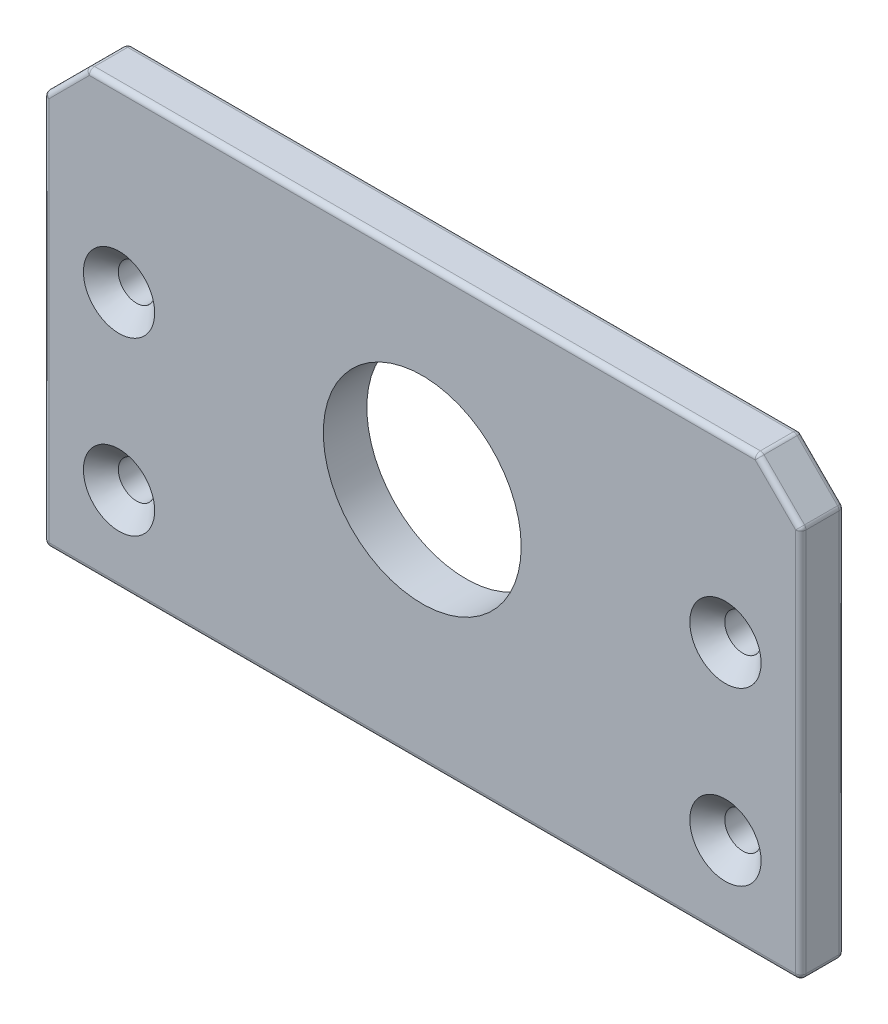
SolidWorks part; units mm, degrees
ref_plane "Front Plane" through (0, 0, 0) normal (0, 0, 1) x (1, 0, 0)
ref_plane "Top Plane" through (0, 0, 0) normal (0, 1, 0) x (1, 0, 0)
ref_plane "Right Plane" through (0, 0, 0) normal (1, 0, 0) x (0, 0, -1)
sketch "Sketch2" plane through (0, 0, 0) normal (0, 1, 0) x (1, 0, 0)
  line L1 (-55.245, 3.175) -> (55.245, 3.175)
  line L2 (-55.245, 3.175) -> (-55.245, -3.175)
  line L3 (-55.245, -3.175) -> (55.245, -3.175)
  line L4 (55.245, 3.175) -> (55.245, -3.175)
  point P4 (0, 3.175)
  point P7 (-55.245, 0)
  dimension "D1" = 6.35
  dimension "D2" = 110.49
extrude "Boss-Extrude1" add sketch "Sketch2" against normal blind 63.5
sketch "Sketch3" plane through (0, 0, 3.175) normal (0, 0, 1) x (1, 0, 0)
  line L2 (-55.245, 0) -> (55.245, 0) construction
  circle A0 centre (0, -28.815) radius 14.4375
  point P2 (0, 0)
  dimension "D1" = 28.815
  dimension "D3" = 28.875
extrude "Cut-Extrude1" cut sketch "Sketch3" against normal through all
chamfer "Chamfer1" distance 6.35 angle 45 2 edges at (-55.245, 0, 0) (55.245, 0, 0)
fillet "Fillet1" [suppressed] radius 0.762
hole_wizard "CBORE for M4 SHCS2" [suppressed] positions "Sketch9" profile "Sketch10" counterbore size "M4" standard "ANSI Metric"
sketch "Sketch9" [suppressed] plane through (0, 0, 3.175) normal (0, 0, 1) x (1, 0, 0)
  line L0 (-48.5794, 0) -> (48.5794, 0) construction
  line L1 (-55.245, -62.738) -> (-55.245, -6.6656) construction
  point P0 (-17.9605, -10.8545)
  dimension "D1" = 10.8545
  dimension "D2" = 37.2845
sketch "Sketch10" plane through (-17.9605, -10.8545, 3.175) normal (1, 0, 0) x (0, -1, 0)
  line L0 (0, 0) -> (0, 6.35)
  line L1 (0, 6.35) -> (2.25, 6.35)
  line L3 (2.25, 6.35) -> (2.25, 4)
  line L4 (2.25, 4) -> (4, 4)
  line L5 (4, 4) -> (4, 0)
  line L7 (4, 0) -> (0, 0)
  line L11 (0, -6.35) -> (0, 107.95) construction
  dimension "Thru Hole Dia." = 4.5
  dimension "Thru Hole Depth" = 6.35
  dimension "C'Bore Dia." = 8
  dimension "C'Bore Depth" = 4
fillet "Fillet2" radius 0.762 18 edges at (0, -63.5, 3.175) (0, -63.5, -3.175) (55.245, -63.5, 0) (55.245, -34.925, 3.175) (55.245, -34.925, -3.175) (52.07, -3.175, -3.175) (55.245, -6.35, 0) (52.07, -3.175, 3.175) (48.895, 0, 0) (0, 0, 3.175) (0, 0, -3.175) (-48.895, 0, 0) (-52.07, -3.175, 3.175) (-52.07, -3.175, -3.175) (-55.245, -63.5, 0) (-55.245, -34.925, -3.175) (-55.245, -6.35, 0) (-55.245, -34.925, 3.175)
sketch "Sketch20" plane through (0, 0, 3.175) normal (0, 0, 1) x (1, 0, 0)
  circle A0 centre (-44.245, -26) radius 3
  circle A1 centre (-44.245, -51) radius 3
  circle A2 centre (44.245, -51) radius 3
  circle A3 centre (44.245, -26) radius 3
  dimension "D3" = 6
  dimension "D1" = 26
  dimension "D2" = 44.245
hole_wizard "CSK for M5 Flat Head Machine Screw1" positions "Sketch21" profile "Sketch22" countersink size "M5" standard "ANSI Metric" end condition through all
sketch "Sketch21" plane through (0, 0, 3.175) normal (0, 0, 1) x (1, 0, 0)
  point P0 (-44.245, -26)
  point P3 (-44.245, -51)
  point P6 (44.245, -51)
  point P9 (44.245, -26)
sketch "Sketch22" plane through (-44.245, -26, 3.175) normal (1, 0, 0) x (0, -1, 0)
  line L0 (0, 0) -> (0, 6.35)
  line L1 (0, 6.35) -> (2.65, 6.35)
  line L2 (2.65, 6.35) -> (2.65, 2.55)
  line L3 (2.65, 2.55) -> (5.2, 0)
  line L5 (5.2, 0) -> (0, 0)
  line L6 (-2.65, 2.55) -> (-5.2, 0) construction
  line L11 (0, -6.35) -> (0, 107.95) construction
  dimension "Thru Hole Dia." = 5.3
  dimension "Thru Hole Depth" = 6.35
  dimension "Near C'Sink Dia." = 10.4
  dimension "Near C'Sink Angle" = 90
